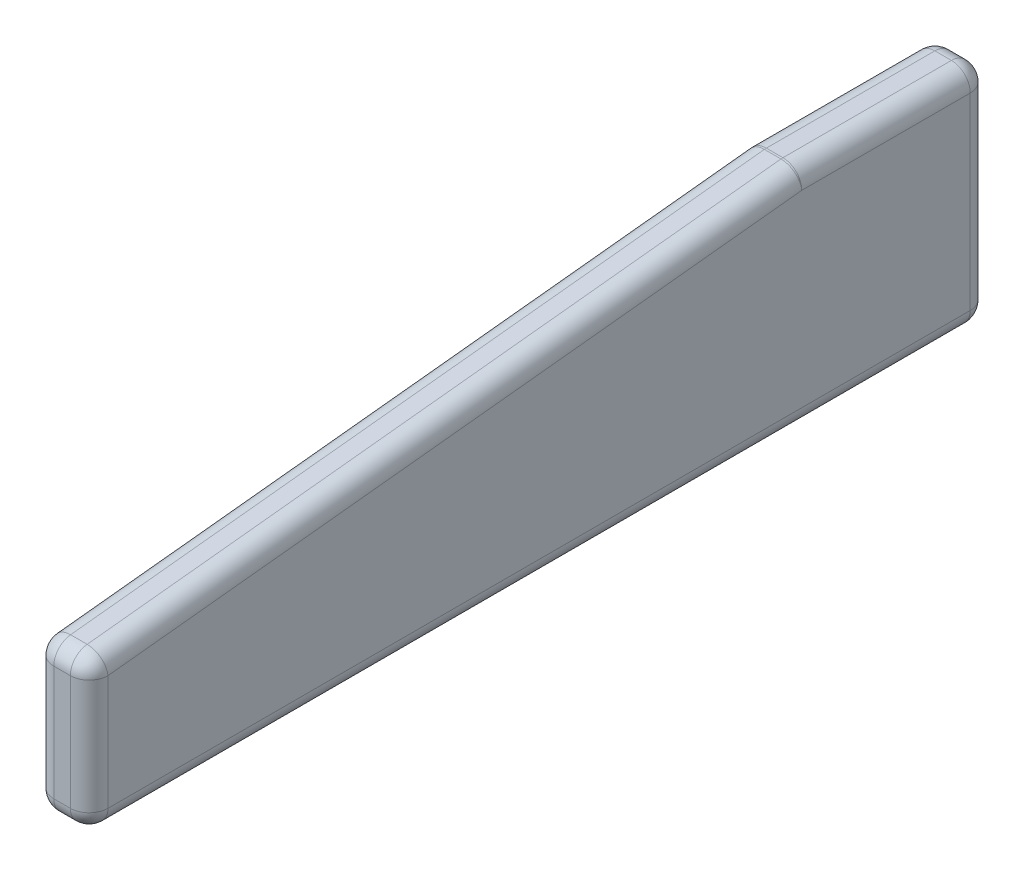
SolidWorks part; units mm, degrees
material "Mahogany"
ref_plane "Front Plane" through (0, 0, 0) normal (0, 0, 1) x (1, 0, 0)
ref_plane "Top Plane" through (0, 0, 0) normal (0, 1, 0) x (1, 0, 0)
ref_plane "Right Plane" through (0, 0, 0) normal (1, 0, 0) x (0, 0, -1)
sketch "Sketch1" plane through (0, 0, 0) normal (1, 0, 0) x (0, 0, -1)
  line L0 (0, 0) -> (0, 84.1309) construction
  line L1 (0, 0) -> (161.7203, 0) construction
  line L2 (-166.9735, -57.6462) -> (123.786, -57.6462)
  line L3 (130.136, -51.2962) -> (130.136, 12.2038)
  line L4 (123.786, 18.5538) -> (66.9711, 18.5538)
  line L5 (66.3027, 18.5185) -> (-167.6419, -6.2448)
  line L6 (-173.3235, -12.5596) -> (-173.3235, -51.2962)
  arc A0 (66.3027, 18.5185) -> (66.9711, 18.5538) centre (66.9711, 12.2038) cw
  arc A1 (123.786, 18.5538) -> (130.136, 12.2038) centre (123.786, 12.2038) cw
  arc A2 (130.136, -51.2962) -> (123.786, -57.6462) centre (123.786, -51.2962) cw
  arc A3 (-166.9735, -57.6462) -> (-173.3235, -51.2962) centre (-166.9735, -51.2962) cw
  arc A4 (-173.3235, -12.5596) -> (-167.6419, -6.2448) centre (-166.9735, -12.5596) cw
  point P11 (66.636, 18.5538)
  point P14 (130.136, 18.5538)
  point P17 (130.136, -57.6462)
  point P20 (-173.3235, -57.6462)
  point P23 (-173.3235, -6.8462)
  dimension "D5" = 6.35
  dimension "D1" = 241.3
  dimension "D2" = 63.5
  dimension "D3" = 76.2
  dimension "D4" = 50.8
extrude "Boss-Extrude1" add sketch "Sketch1" along normal blind 18.288
fillet "Fillet1" radius 6.35 20 edges at (0, 16.6939, -128.2761) (0, -19.5462, -130.136) (0, -55.7864, -128.2761) (0, -57.6462, 21.5938) (0, -55.7864, 171.4636) (0, -31.9279, 173.3235) (0, -8.3123, 171.694) (0, 6.1368, 50.6696) (0, 18.5449, -66.6364) (18.288, 18.5449, -66.6364) (18.288, 18.5538, -95.3785) (18.288, 16.6939, -128.2761) (18.288, -19.5462, -130.136) (18.288, -55.7864, -128.2761) (18.288, -57.6462, 21.5938) (18.288, -55.7864, 171.4636) (18.288, -31.9279, 173.3235) (18.288, -8.3123, 171.694) (0, 18.5538, -95.3785) (18.288, 6.1368, 50.6696)
hole_wizard "3/32 (0.09375) Diameter Hole2" positions "Sketch5" profile "Sketch4" hole size "3/32" standard "ANSI Inch"
sketch "Sketch5" plane through (0, 0, 0) normal (-1, 0, 0) x (0, 0, 1)
  point P0 (16.0223, -10.951)
  point P3 (85.6334, -18.3194)
sketch "Sketch4" plane through (0, -10.951, 16.0223) normal (0, 1, 0) x (0, 0, 1)
  line L0 (0, 0) -> (0, 10.7154)
  line L1 (0, 10.7154) -> (1.1906, 10)
  line L2 (1.1906, 10) -> (1.1906, 0)
  line L5 (1.1906, 0) -> (0, 0)
  line L10 (0, 10.7154) -> (-1.1906, 10) construction
  line L11 (0, -6.35) -> (0, 107.95) construction
  dimension "Hole Dia." = 2.3812
  dimension "Hole Depth" = 10
  dimension "Drill Angle" = 118
hole_wizard "3/32 (0.09375) Diameter Hole3" positions "Sketch7" profile "Sketch6" hole size "3/32" standard "ANSI Inch"
sketch "Sketch7" plane through (0, 0, 0) normal (-1, 0, 0) x (0, 0, 1)
  point P0 (158.0748, -26.7962)
  point P3 (-114.9252, -6.7962)
sketch "Sketch6" plane through (0, -26.7962, 158.0748) normal (0, 1, 0) x (0, 0, 1)
  line L0 (0, 0) -> (0, 10.6214)
  line L1 (0, 10.6214) -> (1.1906, 9.906)
  line L2 (1.1906, 9.906) -> (1.1906, 0)
  line L5 (1.1906, 0) -> (0, 0)
  line L10 (0, 10.6214) -> (-1.1906, 9.906) construction
  line L11 (0, -6.35) -> (0, 107.95) construction
  dimension "Hole Dia." = 2.3812
  dimension "Hole Depth" = 9.906
  dimension "Drill Angle" = 118
hole_wizard "3/32 (0.09375) Diameter Hole4" positions "Sketch11" profile "Sketch10" hole size "3/32" standard "ANSI Inch"
sketch "Sketch11" plane through (0, 0, 0) normal (-1, 0, 0) x (0, 0, 1)
  point P0 (-93.9245, -45.2962)
  point P3 (-18.9245, -45.2962)
  point P6 (62.0748, -45.2962)
  point P9 (137.0748, -45.2962)
sketch "Sketch10" plane through (0, -45.2962, -93.9245) normal (0, 1, 0) x (0, 0, 1)
  line L0 (0, 0) -> (0, 10.6214)
  line L1 (0, 10.6214) -> (1.1906, 9.906)
  line L2 (1.1906, 9.906) -> (1.1906, 0)
  line L5 (1.1906, 0) -> (0, 0)
  line L10 (0, 10.6214) -> (-1.1906, 9.906) construction
  line L11 (0, -6.35) -> (0, 107.95) construction
  dimension "Hole Dia." = 2.3812
  dimension "Hole Depth" = 9.906
  dimension "Drill Angle" = 118
hole_wizard "3/32 (0.09375) Diameter Hole5" positions "Sketch13" profile "Sketch12" hole size "3/32" standard "ANSI Inch"
sketch "Sketch13" plane through (0, 0, 0) normal (-1, 0, 0) x (0, 0, 1)
  point P0 (-87.9313, 7.1638)
  point P3 (0.4561, -0.0016)
  point P6 (99.8304, -10.5205)
sketch "Sketch12" plane through (0, 7.1638, -87.9313) normal (0, 1, 0) x (0, 0, 1)
  line L0 (0, 0) -> (0, 10.7154)
  line L1 (0, 10.7154) -> (1.1906, 10)
  line L2 (1.1906, 10) -> (1.1906, 0)
  line L5 (1.1906, 0) -> (0, 0)
  line L10 (0, 10.7154) -> (-1.1906, 10) construction
  line L11 (0, -6.35) -> (0, 107.95) construction
  dimension "Hole Dia." = 2.3812
  dimension "Hole Depth" = 10
  dimension "Drill Angle" = 118
